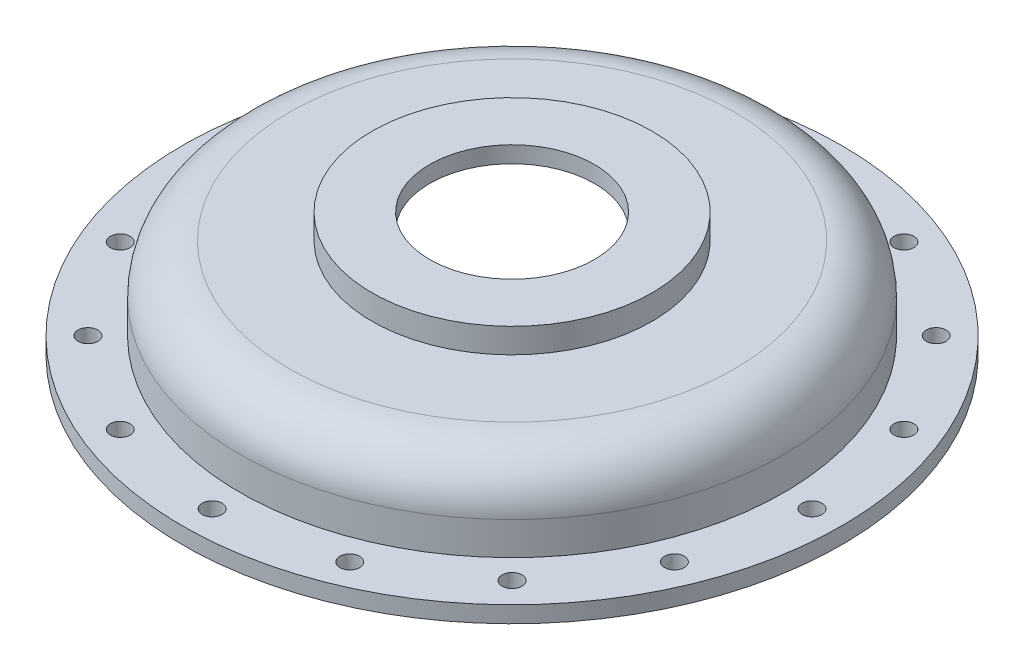
SolidWorks part; units mm, degrees
ref_plane "Front Plane" through (0, 0, 0) normal (0, 0, 1) x (1, 0, 0)
ref_plane "Top Plane" through (0, 0, 0) normal (0, 1, 0) x (1, 0, 0)
ref_plane "Right Plane" through (0, 0, 0) normal (1, 0, 0) x (0, 0, -1)
sketch "Sketch1" plane through (0, 0, 0) normal (0, 0, 1) x (1, 0, 0)
  line L0 (0, 0) -> (0, 3534.2286) construction
  line L1 (0, 1905) -> (2159, 1905)
  line L2 (2159, 1905) -> (2159, 1524)
  line L3 (2159, 1524) -> (3429, 1524)
  line L4 (4191, 762) -> (4191, 254)
  line L5 (4191, 254) -> (5080, 254)
  line L6 (5080, 254) -> (5080, 0)
  line L7 (5080, 0) -> (3937, 0)
  line L8 (3937, 0) -> (3937, 508)
  line L9 (3175, 1270) -> (1905, 1270)
  line L10 (1905, 1270) -> (1905, 1651)
  line L11 (1905, 1651) -> (0, 1651)
  line L12 (0, 1651) -> (0, 1905)
  arc A0 (3937, 508) -> (3175, 1270) centre (3175, 508) ccw
  arc A1 (4191, 762) -> (3429, 1524) centre (3429, 762) ccw
  dimension "D11" = 762
  dimension "D1" = 254
  dimension "D2" = 254
  dimension "D3" = 254
  dimension "D4" = 254
  dimension "D5" = 254
  dimension "D6" = 381
  dimension "D7" = 1905
  dimension "D8" = 10160
  dimension "D9" = 8382
  dimension "D10" = 4318
revolve "Revolve2" add sketch "Sketch1" angle 360 about L0
sketch "Sketch4" plane through (0, 1905, 0) normal (0, 1, 0) x (1, 0, 0)
  circle A0 centre (0, 0) radius 1270
  dimension "D1" = 2540
extrude "Cut-Extrude3" cut sketch "Sketch4" against normal through all
sketch "Sketch5" plane through (0, 254, 0) normal (0, 1, 0) x (1, 0, 0)
  circle A0 centre (0, 4622.8) radius 152.4
  dimension "D2" = 304.8
  dimension "D1" = 4622.8
extrude "Cut-Extrude4" cut sketch "Sketch5" against normal through all
pattern_circular "CirPattern2" count 16 over 360 about axis through (0, 0, 0) along (0, 1, 0) of "Cut-Extrude4"
